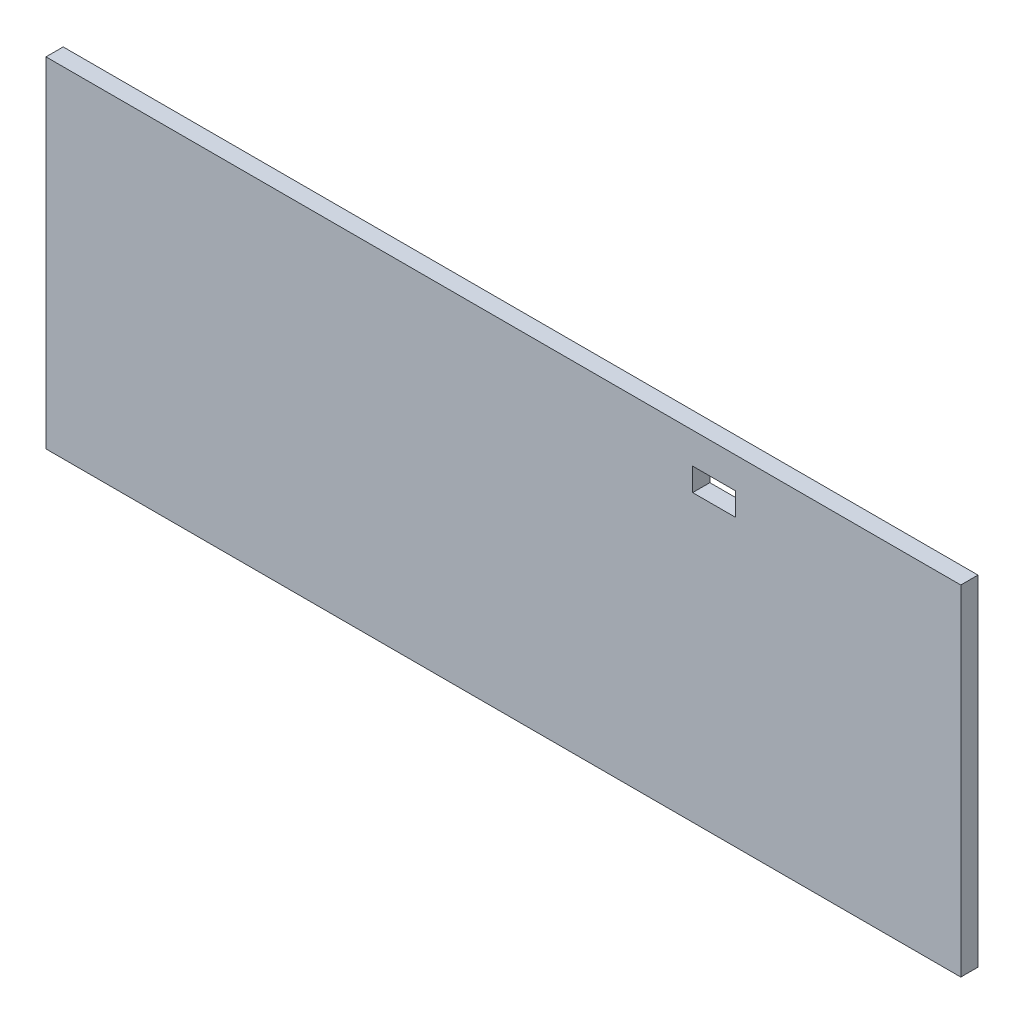
SolidWorks part; units mm, degrees
ref_plane "Plan de face" through (0, 0, 0) normal (0, 0, 1) x (1, 0, 0)
ref_plane "Plan de dessus" through (0, 0, 0) normal (0, 1, 0) x (1, 0, 0)
ref_plane "Plan de droite" through (0, 0, 0) normal (1, 0, 0) x (0, 0, -1)
sketch "Esquisse1" plane through (0, 0, 0) normal (0, 0, 1) x (1, 0, 0)
  line L0 (-6, -112.4149) -> (0, -112.4149) construction
  line L1 (-6, 6) -> (313, 6)
  line L2 (-6, 6) -> (-6, -112.4149)
  line L3 (-6, -112.4149) -> (313, -112.4149)
  line L4 (313, 6) -> (313, -112.4149)
  line L5 (313, 6) -> (313, 0) construction
extrude "Boss.-Extru.1" add sketch "Esquisse1" along normal blind 6
sketch "Esquisse2" plane through (0, 0, 0) normal (0, 0, -1) x (-1, 0, 0)
  line L1 (-219.5, -12.85) -> (-234.5, -12.85)
  line L2 (-219.5, -12.85) -> (-219.5, -4.85)
  line L3 (-219.5, -4.85) -> (-234.5, -4.85)
  line L4 (-234.5, -12.85) -> (-234.5, -4.85)
  line L5 (-227, -10.1) -> (-227, -12.85) construction
  line L7 (-223, -8.85) -> (-219.5, -8.85) construction
  line L8 (-223, -10.1) -> (-223, -7.6) construction
  line L9 (-223, -10.1) -> (-231, -10.1) construction
  dimension "D1" = 15
  dimension "D2" = 8
extrude "Enlèv. mat.-Extru.1" cut sketch "Esquisse2" against normal up to next contours L2 L1 L4 L3
